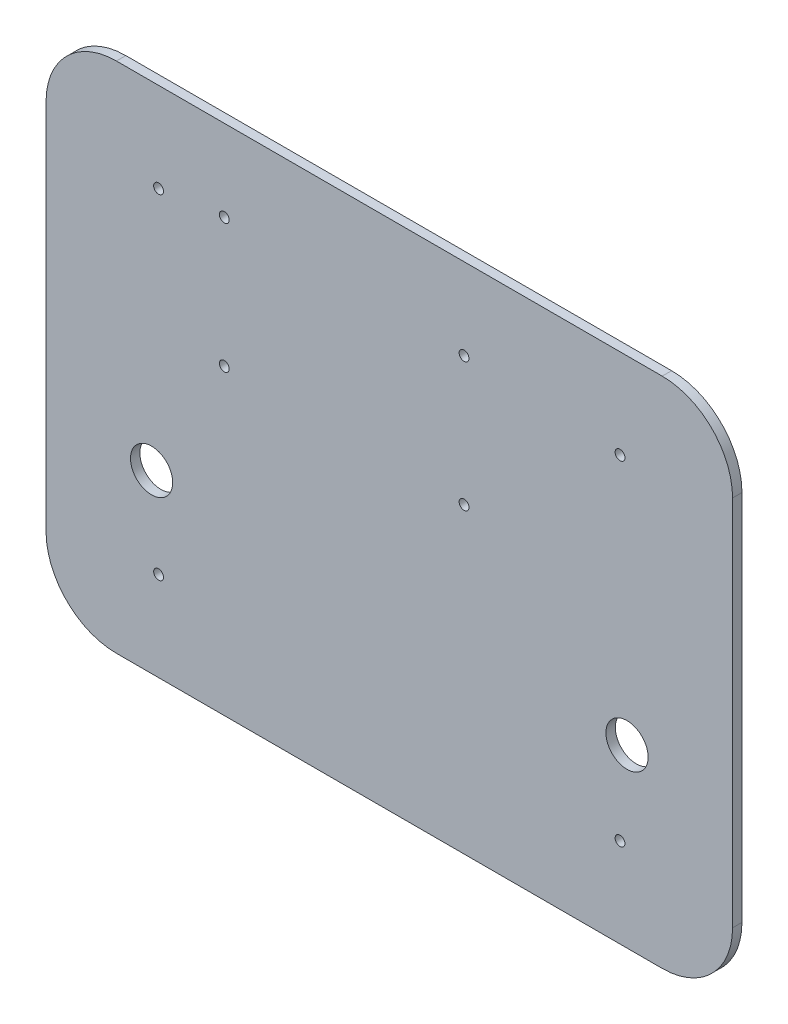
SolidWorks part; units mm, degrees
ref_plane "Front Plane" through (0, 0, 0) normal (0, 0, 1) x (1, 0, 0)
ref_plane "Top Plane" through (0, 0, 0) normal (0, 1, 0) x (1, 0, 0)
ref_plane "Right Plane" through (0, 0, 0) normal (1, 0, 0) x (0, 0, -1)
sketch "Sketch1" plane through (0, 0, 0) normal (0, 0, 1) x (1, 0, 0)
  line L1 (-116.36, -109.36) -> (116.36, -109.36)
  line L2 (-146.36, -79.36) -> (-146.36, 79.36)
  line L3 (-116.36, 109.36) -> (116.36, 109.36)
  line L4 (146.36, -79.36) -> (146.36, 79.36)
  line L5 (-146.36, -109.36) -> (146.36, 109.36) construction
  line L6 (-146.36, 109.36) -> (146.36, -109.36) construction
  line L16 (90.935, -60.915) -> (105.815, -60.915) construction
  line L17 (105.815, -81.585) -> (90.935, -81.585) construction
  line L18 (90.935, 81.585) -> (105.815, 81.585) construction
  line L19 (105.815, 60.915) -> (90.935, 60.915) construction
  line L20 (-105.815, -60.915) -> (-90.935, -60.915) construction
  line L21 (-90.935, -81.585) -> (-105.815, -81.585) construction
  line L22 (-105.815, 81.585) -> (-90.935, 81.585) construction
  line L23 (-90.935, 60.915) -> (-105.815, 60.915) construction
  line L24 (-98.375, 81.585) -> (-98.375, -81.585) construction
  line L25 (98.375, 81.585) -> (98.375, -81.585) construction
  line L26 (116.15, 71.25) -> (-116.15, 71.25) construction
  line L27 (-116.15, -71.25) -> (116.15, -71.25) construction
  arc A0 (-116.36, -109.36) -> (-146.36, -79.36) centre (-116.36, -79.36) cw
  arc A1 (116.36, -109.36) -> (146.36, -79.36) centre (116.36, -79.36) ccw
  arc A2 (116.36, 109.36) -> (146.36, 79.36) centre (116.36, 79.36) cw
  arc A3 (-146.36, 79.36) -> (-116.36, 109.36) centre (-116.36, 79.36) cw
  circle A4 centre (-101.36, -34.36) radius 9
  circle A5 centre (101.36, -34.36) radius 9
  circle A6 centre (-98.375, 71.25) radius 2.1
  circle A7 centre (98.375, 71.25) radius 2.1
  circle A8 centre (98.375, -71.25) radius 2.1
  circle A9 centre (-98.375, -71.25) radius 2.1
  arc A18 (105.815, -81.585) -> (105.815, -60.915) centre (105.815, -71.25) ccw construction
  arc A19 (90.935, -60.915) -> (90.935, -81.585) centre (90.935, -71.25) ccw construction
  arc A20 (105.815, 60.915) -> (105.815, 81.585) centre (105.815, 71.25) ccw construction
  arc A21 (90.935, 81.585) -> (90.935, 60.915) centre (90.935, 71.25) ccw construction
  arc A22 (-90.935, -81.585) -> (-90.935, -60.915) centre (-90.935, -71.25) ccw construction
  arc A23 (-105.815, -60.915) -> (-105.815, -81.585) centre (-105.815, -71.25) ccw construction
  arc A24 (-90.935, 60.915) -> (-90.935, 81.585) centre (-90.935, 71.25) ccw construction
  arc A25 (-105.815, 81.585) -> (-105.815, 60.915) centre (-105.815, 71.25) ccw construction
  point P0 (0, 0)
  point P66 (0, 0)
  point P67 (0, 0)
  point P68 (0, 0)
  dimension "D3" = 30
  dimension "D4" = 18
  dimension "D8" = 4.2
  dimension "D5" = 45
  dimension "D6" = 45
  dimension "D7" = 75
extrude "Boss-Extrude1" add sketch "Sketch1" along normal blind 4
sketch "Sketch2" plane through (0, 0, 4) normal (0, 0, 1) x (1, 0, 0)
  circle A1 centre (-70.36, 19.66) radius 2.1
  circle A2 centre (-70.36, 19.66) radius 2.1
  circle A3 centre (-70.36, 19.66) radius 4
  circle A4 centre (-70.36, 19.66) radius 4
  circle A5 centre (-70.36, 74.66) radius 4
  circle A6 centre (-70.36, 74.66) radius 4
  circle A7 centre (-70.36, 74.66) radius 2.1
  circle A8 centre (-70.36, 74.66) radius 2.1
  circle A9 centre (31.86, 19.66) radius 2.1
  circle A10 centre (31.86, 19.66) radius 2.1
  circle A11 centre (31.86, 19.66) radius 4
  circle A12 centre (31.86, 19.66) radius 4
  circle A13 centre (31.86, 74.66) radius 4
  circle A14 centre (31.86, 74.66) radius 4
  circle A15 centre (31.86, 74.66) radius 2.1
  circle A16 centre (31.86, 74.66) radius 2.1
  dimension "D1" = 0
  dimension "D2" = 0
  dimension "D3" = 0
  dimension "D4" = 0
  dimension "D5" = 0
  dimension "D6" = 0
  dimension "D7" = 0
  dimension "D8" = 0
extrude "Cut-Extrude1" cut sketch "Sketch2" against normal through all contours A8 | A2 | A16 | A10
